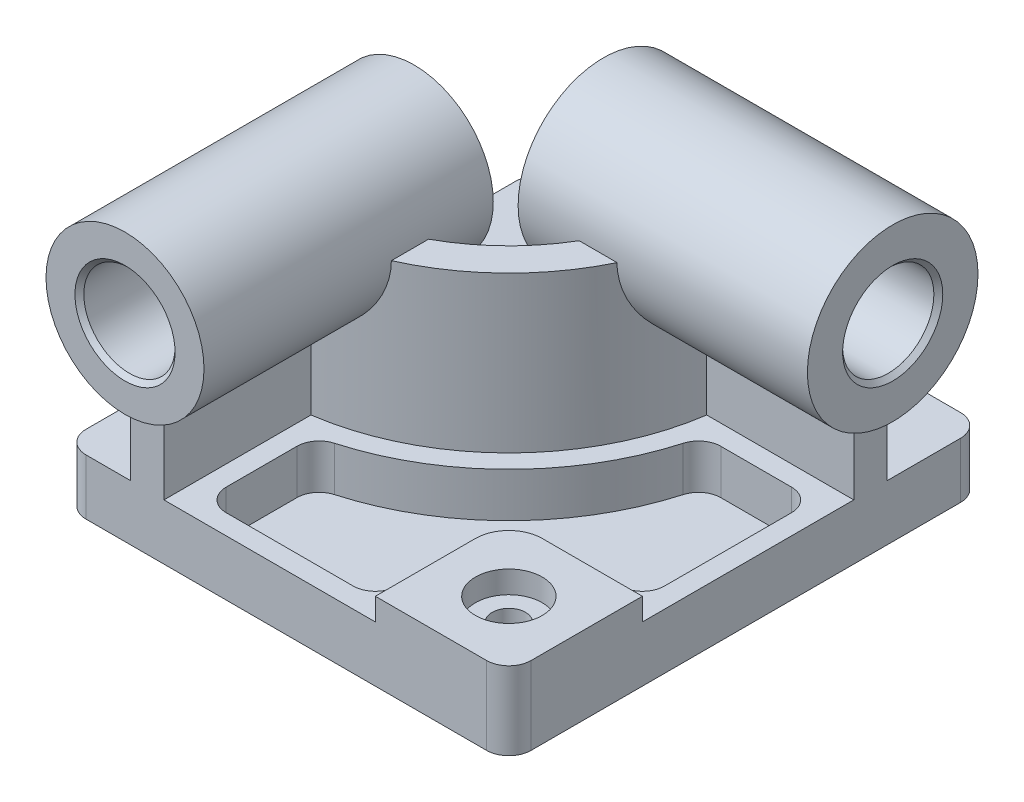
SolidWorks part; units mm, degrees
material "Alloy Steel"
ref_plane "Front Plane" through (0, 0, 0) normal (0, 0, 1) x (1, 0, 0)
ref_plane "Top Plane" through (0, 0, 0) normal (0, 1, 0) x (1, 0, 0)
ref_plane "Right Plane" through (0, 0, 0) normal (1, 0, 0) x (0, 0, -1)
sketch "Sketch1" plane through (0, 0, 0) normal (0, 1, 0) x (1, 0, 0)
  line L0 (0, 0) -> (0, -170) construction
  line L1 (-20, 43) -> (160, 43)
  line L2 (-30, 33) -> (-30, -160)
  line L3 (-20, -170) -> (160, -170)
  line L4 (170, 33) -> (170, -160)
  line L6 (21.1729, -100.3509) -> (22.0551, -100.3509) construction
  line L8 (0, 0) -> (170, 0) construction
  arc A0 (-20, 43) -> (-30, 33) centre (-20, 33) ccw
  arc A1 (-30, -160) -> (-20, -170) centre (-20, -160) ccw
  arc A2 (160, -170) -> (170, -160) centre (160, -160) ccw
  arc A3 (160, 43) -> (170, 33) centre (160, 33) cw
  dimension "D5" = 10
  dimension "D1" = 170
  dimension "D2" = 170
  dimension "D3" = 213
  dimension "D4" = 200
extrude "Boss-Extrude1" add sketch "Sketch1" along normal blind 25
sketch "Sketch2" plane through (0, 25, 0) normal (0, 1, 0) x (1, 0, 0)
  line L0 (0, -90) -> (0, -170)
  line L1 (-20, -170) -> (160, -170) construction
  line L2 (90, 0) -> (170, 0)
  line L3 (170, -160) -> (170, 33) construction
  line L4 (15, -103.923) -> (15, -170)
  line L5 (103.923, -15) -> (170, -15)
  line L6 (170, 0) -> (170, -15)
  line L7 (0, -170) -> (15, -170)
  arc A0 (0, -90) -> (90, 0) centre (0, 0) ccw
  arc A1 (15, -103.923) -> (103.923, -15) centre (0, 0) ccw
  dimension "D1" = 80
  dimension "D2" = 15
extrude "Boss-Extrude2" add sketch "Sketch2" along normal blind 95 from surface at -25 starting at face at (70, 0, 63.5)
sketch "Sketch3" plane through (0, 25, 0) normal (0, 1, 0) x (1, 0, 0)
  line L0 (15, -170) -> (160, -170) construction
  line L1 (125, -110) -> (170, -110)
  line L2 (110, -125) -> (110, -170)
  line L3 (110, -170) -> (160, -170)
  line L4 (170, -110) -> (170, -160)
  line L5 (170, -160) -> (170, -15) construction
  arc A0 (160, -170) -> (170, -160) centre (160, -160) ccw construction
  arc A1 (160, -170) -> (170, -160) centre (160, -160) ccw
  arc A2 (125, -110) -> (110, -125) centre (125, -125) ccw
  dimension "D3" = 15
  dimension "D1" = 60
  dimension "D2" = 60
extrude "Boss-Extrude3" add sketch "Sketch3" along normal blind 10
hole_wizard "CBORE for M8 Hex Head Bolt1" positions "Sketch5" profile "Sketch4" counterbore size "M8" standard "ANSI Metric" end condition through all
sketch "Sketch5" plane through (0, 35, 0) normal (0, 1, 0) x (1, 0, 0)
  line L0 (110, -170) -> (160, -170) construction
  line L2 (170, -160) -> (170, -110) construction
  point P0 (140, -140)
  dimension "D1" = 30
  dimension "D2" = 30
sketch "Sketch4" plane through (140, 35, 140) normal (1, 0, 0) x (0, 0, 1)
  line L0 (0, 0) -> (0, 35)
  line L1 (0, 35) -> (7.5, 35)
  line L3 (7.5, 35) -> (7.5, 10)
  line L4 (7.5, 10) -> (15, 10)
  line L5 (15, 10) -> (15, 0)
  line L7 (15, 0) -> (0, 0)
  line L11 (0, -6.35) -> (0, 107.95) construction
  dimension "Thru Hole Dia." = 15
  dimension "Thru Hole Depth" = 35
  dimension "C'Bore Dia." = 30
  dimension "C'Bore Depth" = 10
sketch "Sketch6" plane through (0, 25, 0) normal (0, 1, 0) x (1, 0, 0)
  line L0 (15, -170) -> (110, -170) construction
  line L1 (110, -170) -> (110, -125) construction
  line L2 (125, -110) -> (170, -110) construction
  line L3 (170, -110) -> (170, -15) construction
  line L4 (170, -15) -> (103.923, -15) construction
  line L5 (15, -103.923) -> (15, -170) construction
  line L6 (101, -161) -> (101, -125)
  line L7 (101, -151) -> (101, -125)
  line L8 (125, -101) -> (161, -101)
  line L9 (125, -101) -> (151, -101)
  line L10 (161, -24) -> (111.4451, -24)
  line L11 (151, -24) -> (119.2476, -24)
  line L12 (24, -161) -> (101, -161)
  line L13 (24, -111.4451) -> (24, -161)
  line L14 (24, -119.2476) -> (24, -151)
  line L15 (161, -101) -> (161, -24)
  line L18 (34, -161) -> (91, -161)
  line L21 (161, -91) -> (161, -34)
  arc A0 (161, -91) -> (151, -101) centre (151, -91) cw
  arc A1 (101, -151) -> (91, -161) centre (91, -151) cw
  arc A2 (24, -119.2476) -> (31.2581, -109.6309) centre (34, -119.2476) cw
  arc A3 (109.6309, -31.2581) -> (119.2476, -24) centre (119.2476, -34) cw
  arc A4 (125, -101) -> (101, -125) centre (125, -125) ccw
  arc A5 (24, -111.4451) -> (111.4451, -24) centre (0, 0) ccw
  arc A6 (125, -101) -> (101, -125) centre (125, -125) ccw
  arc A7 (31.2581, -109.6309) -> (109.6309, -31.2581) centre (0, 0) ccw
  arc A8 (161, -34) -> (151, -24) centre (151, -34) ccw
  arc A9 (34, -161) -> (24, -151) centre (34, -151) cw
  arc A10 (125, -110) -> (110, -125) centre (125, -125) ccw construction
  arc A11 (15, -103.923) -> (103.923, -15) centre (0, 0) ccw construction
  dimension "D2" = 10
  dimension "D3" = 10
  dimension "D1" = 9
extrude "Cut-Extrude1" cut sketch "Sketch6" against normal offset from surface (20 mm away) 5 up to face at (140, 0, 147.5)
sketch "Sketch7" plane through (0, 0, 170) normal (0, 0, 1) x (1, 0, 0)
  line L0 (0, 95) -> (15, 95) construction
  circle A0 centre (7.5, 95) radius 35.5
  dimension "D1" = 71
extrude "Boss-Extrude4" add sketch "Sketch7" against normal blind 130 from offset 10
sketch "Sketch8" plane through (170, 0, 0) normal (1, 0, 0) x (0, 0, -1)
  line L0 (-15, 95) -> (0, 95) construction
  circle A0 centre (-7.5, 95) radius 38.3333
  dimension "D1" = 76.6667
extrude "Boss-Extrude5" add sketch "Sketch8" against normal blind 130 from offset 10
sketch "Sketch9" plane through (0, 0, 180) normal (0, 0, 1) x (1, 0, 0)
  circle A0 centre (7.5, 95) radius 20.5
  dimension "D1" = 41
extrude "Cut-Extrude2" cut sketch "Sketch9" against normal up to next
sketch "Sketch10" plane through (180, 0, 0) normal (1, 0, 0) x (0, 0, -1)
  circle A0 centre (-7.5, 95) radius 20.5
  dimension "D1" = 41
extrude "Cut-Extrude3" cut sketch "Sketch10" against normal up to next
chamfer "Chamfer1" distance 2 angle 45 4 edges at (50, 95, -13) (28, 95, 50) (180, 95, -13) (28, 95, 180)
equation "\"A\"= 213"
equation "\"D1@Sketch1\"=\"C\""
equation "\"D2@Sketch1\"=\"C\""
equation "\"B\"= 200"
equation "\"D3@Sketch1\"=\"A\""
equation "\"C\"= 170"
equation "\"D4@Sketch1\"=\"B\""
equation "\"D1@Sketch7\"=\"X\""
equation "\"D\"= 130"
equation "\"D1@Boss-Extrude4\"=\"D\""
equation "\"D1@Sketch8\"=\"Y\""
equation "\"D1@Boss-Extrude5\"=\"D\""
equation "\"E\"= 41"
equation "\"D1@Sketch9\"=\"E\""
equation "\"D1@Sketch10\"=\"E\""
equation "\"X\"= \"A\" / 3"
equation "\"Y\"= \"B\" / 3 + 10"
